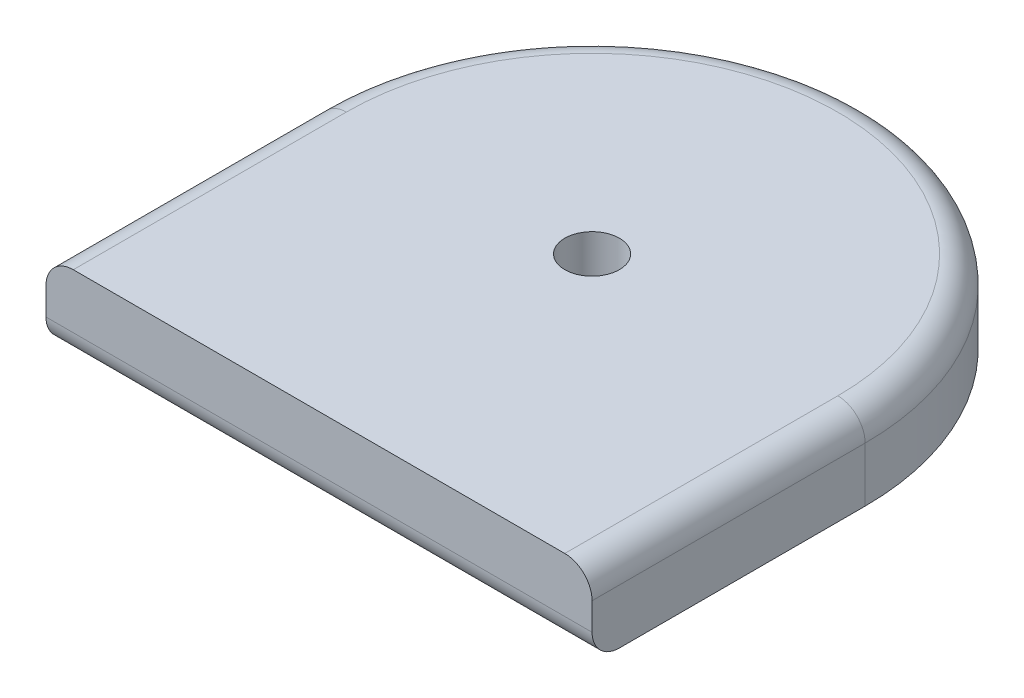
SolidWorks part; units mm, degrees
ref_plane "Front Plane" through (0, 0, 0) normal (0, 0, 1) x (1, 0, 0)
ref_plane "Top Plane" through (0, 0, 0) normal (0, 1, 0) x (1, 0, 0)
ref_plane "Right Plane" through (0, 0, 0) normal (1, 0, 0) x (0, 0, -1)
sketch "Sketch1" plane through (0, 0, 0) normal (0, 1, 0) x (1, 0, 0)
  line L0 (-10, 0) -> (-10, -10)
  line L1 (-10, -10) -> (10, -10)
  line L2 (10, -10) -> (10, 0)
  arc A0 (-10, 0) -> (10, 0) centre (0, 0) cw
  dimension "D1" = 10
  dimension "D2" = 10
extrude "Boss-Extrude1" add sketch "Sketch1" along normal blind 3
sketch "Sketch2" plane through (0, 3, 0) normal (0, 1, 0) x (1, 0, 0)
  circle A0 centre (0, 0) radius 1
  dimension "D1" = 2
extrude "Cut-Extrude1" cut sketch "Sketch2" against normal through all
fillet "Fillet1" radius 1 4 edges at (10, 3, 5) (-10, 3, 5) (0, 3, -10) (0, 0, 10)
